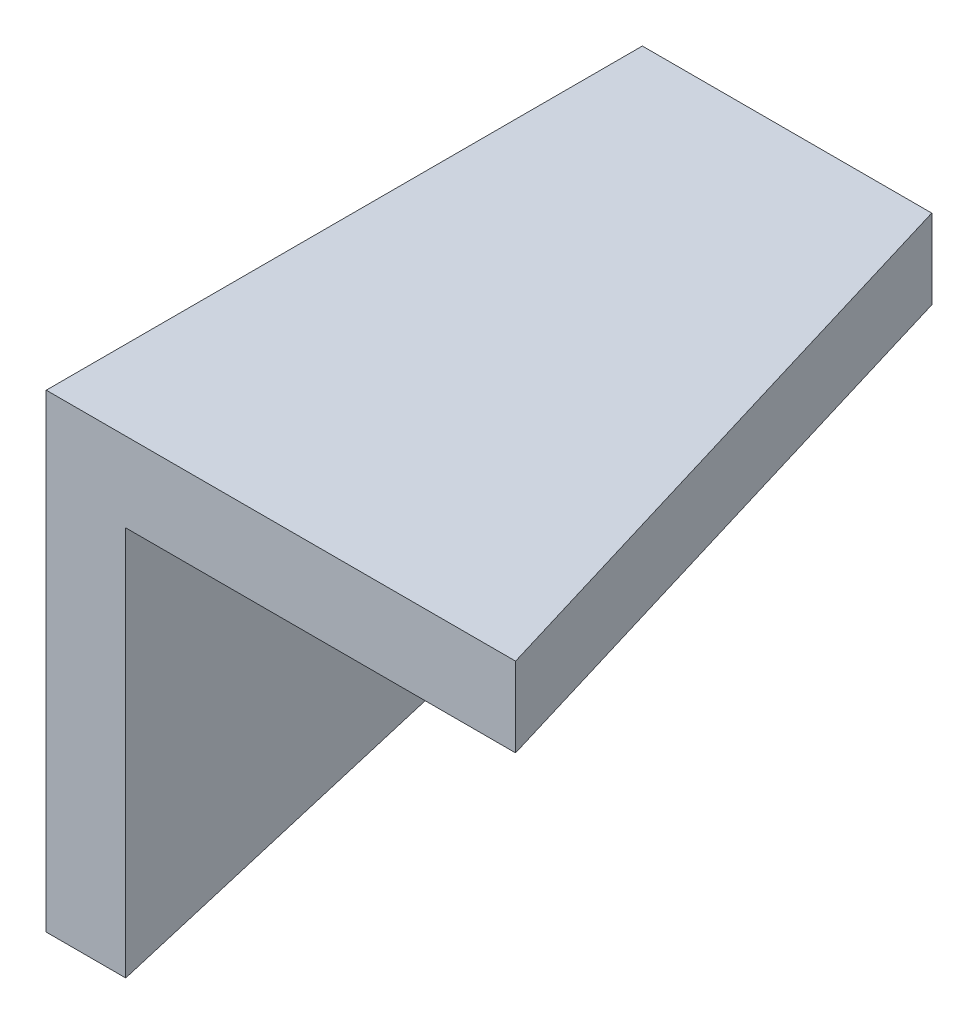
SolidWorks part; units mm, degrees
material "PLA"
ref_plane "Front Plane" through (0, 0, 0) normal (0, 0, 1) x (1, 0, 0)
ref_plane "Top Plane" through (0, 0, 0) normal (0, 1, 0) x (1, 0, 0)
ref_plane "Right Plane" through (0, 0, 0) normal (1, 0, 0) x (0, 0, -1)
sketch "Sketch1" plane through (0, 0, 0) normal (0, 0, 1) x (1, 0, 0)
  line L0 (40, 0) -> (0, 0)
  line L1 (0, 0) -> (0, -40)
  line L2 (40, 8) -> (-8, 8)
  line L3 (-8, 8) -> (-8, -40)
  line L4 (40, 0) -> (40, 8)
  line L5 (0, -40) -> (-8, -40)
  dimension "D1" = 40
  dimension "D2" = 40
  dimension "D3" = 8
extrude "Boss-Extrude1" add sketch "Sketch1" along normal mid plane 60
sketch "Sketch2" plane through (0, 0, 0) normal (0, -1, 0) x (1, 0, 0)
  line L0 (39.2402, 30) -> (21.1294, -30)
  line L1 (0, 30) -> (40, 30) construction
  line L2 (175.2248, 480.5068) -> (3.175, -89.4815) construction
  line L3 (0, -30) -> (40, -30) construction
  line L4 (21.1294, -30) -> (40, -30)
  line L5 (40, -30) -> (40, 30)
  line L6 (40, 30) -> (39.2402, 30)
extrude "Cut-Extrude1" cut sketch "Sketch2" against normal blind 10
sketch "Sketch4" plane through (0, 0, -30) normal (0, 0, -1) x (-1, 0, 0)
  line L0 (0, 0) -> (8, 8)
  line L1 (0, 0) -> (0, -40)
  line L2 (0, -40) -> (8, -40)
  line L3 (8, -40) -> (8, 8)
extrude "Cut-Extrude2" cut sketch "Sketch4" against normal through all
mirror "Mirror1" about plane through (0, 0, 30) normal (0.7071, 0.7071, 0) of bodies 104
